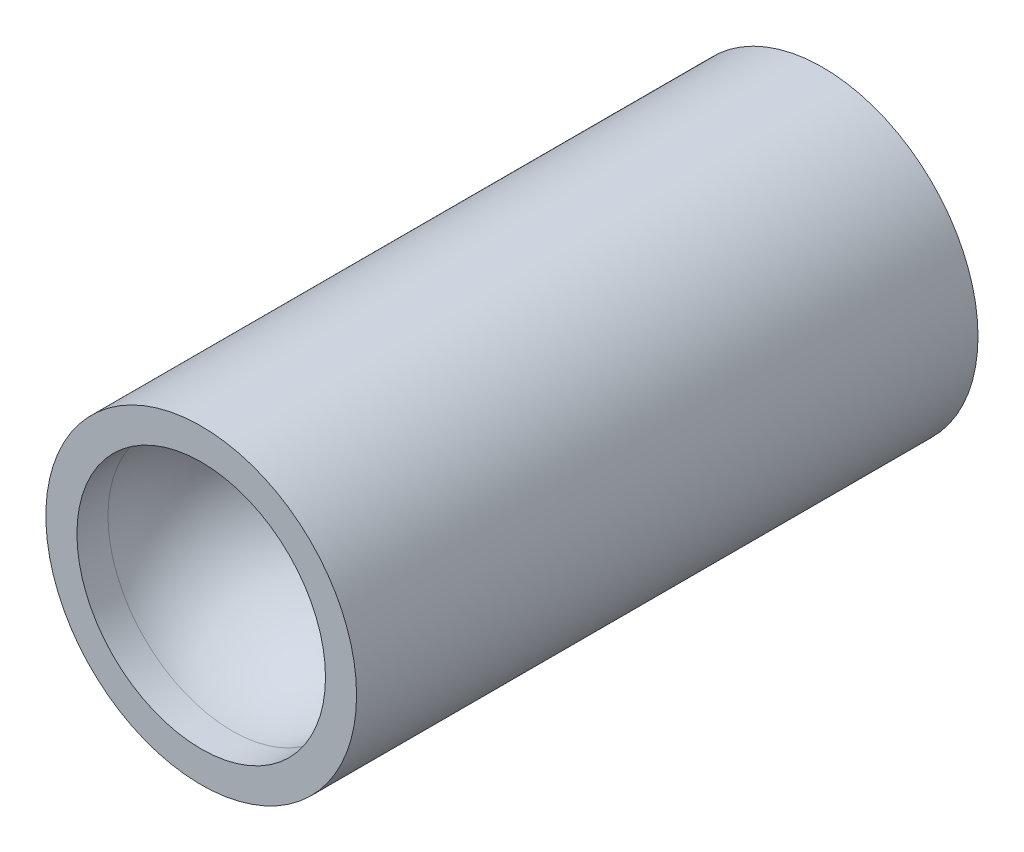
SolidWorks part; units mm, degrees
ref_plane "Piano frontale" through (0, 0, 0) normal (0, 0, 1) x (1, 0, 0)
ref_plane "Piano superiore" through (0, 0, 0) normal (0, 1, 0) x (1, 0, 0)
ref_plane "Piano destro" through (0, 0, 0) normal (1, 0, 0) x (0, 0, -1)
sketch "Schizzo1" plane through (0, 0, 0) normal (0, 0, 1) x (1, 0, 0)
  circle A0 centre (0, 0) radius 5
  dimension "D1" = 10
extrude "Estrusione-Estrusione1" add sketch "Schizzo1" along normal blind 20
cosmetic thread "Filettatura cosmetica1" parameters "D1"=10, "D2"=8.344
sketch "Schizzo2" plane through (0, 0, 20) normal (0, 0, 1) x (1, 0, 0)
  circle A1 centre (0, 0) radius 4
  dimension "D1" = 8
extrude "Taglio-Estrusione1" cut sketch "Schizzo2" against normal blind 1
sketch "Schizzo15" plane through (0, 0, 19) normal (0, 0, 1) x (1, 0, 0)
  line L0 (0, -4) -> (0, 4)
  arc A0 (0, 4) -> (0, -4) centre (0, 0) ccw
  dimension "D1" = 4
revolve "Taglia-Rivoluzione2" cut sketch "Schizzo15" angle 360 about L0
